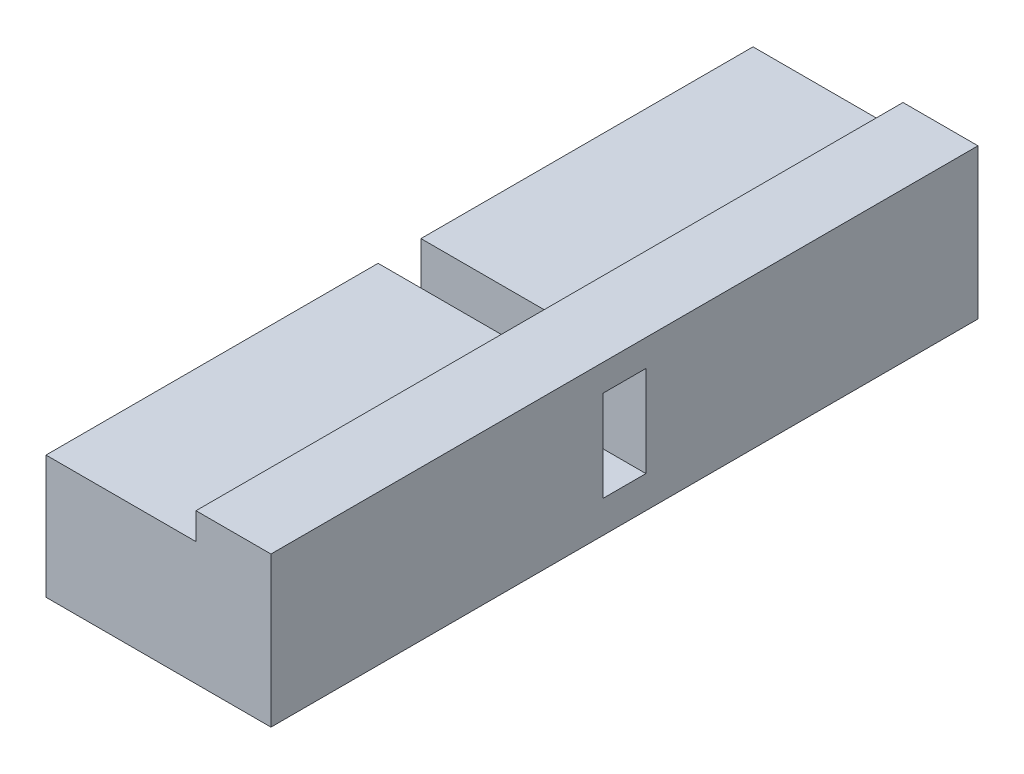
SolidWorks part; units mm, degrees
ref_plane "Front Plane" through (0, 0, 0) normal (0, 0, 1) x (1, 0, 0)
ref_plane "Top Plane" through (0, 0, 0) normal (0, 1, 0) x (1, 0, 0)
ref_plane "Right Plane" through (0, 0, 0) normal (1, 0, 0) x (0, 0, -1)
sketch "SK_P01_Carrier" plane through (0, 0, 0) normal (0, 1, 0) x (1, 0, 0)
  line L0 (-10.5, -33) -> (10.5, -33)
  line L1 (10.5, -33) -> (10.5, 33)
  line L2 (10.5, 33) -> (-10.5, 33)
  line L3 (-10.5, 33) -> (-10.5, -33)
extrude "P01_Carrier" add sketch "SK_P01_Carrier" along normal blind 3
sketch "SK_P02_WAGO221415GNDstar" plane through (0, 0, 0) normal (0, 1, 0) x (1, 0, 0)
  line L0 (-10.5, 2) -> (10.5, 2)
  line L1 (10.5, 2) -> (10.5, 33)
  line L2 (10.5, 33) -> (-10.5, 33)
  line L3 (-10.5, 33) -> (-10.5, 2)
extrude "P02_WAGO221415GNDstar" add sketch "SK_P02_WAGO221415GNDstar" along normal blind 8.5 from offset 3
sketch "SK_P03_WAGO221415packnode" plane through (0, 0, 0) normal (0, 1, 0) x (1, 0, 0)
  line L0 (-10.5, -33) -> (10.5, -33)
  line L1 (10.5, -33) -> (10.5, -2)
  line L2 (10.5, -2) -> (-10.5, -2)
  line L3 (-10.5, -2) -> (-10.5, -33)
extrude "P03_WAGO221415packnode" add sketch "SK_P03_WAGO221415packnode" along normal blind 8.5 from offset 3
sketch "SK_P04_Levers" plane through (0, 0, 0) normal (0, 1, 0) x (1, 0, 0)
  line L0 (3.5, -33) -> (10.5, -33)
  line L1 (10.5, -33) -> (10.5, 33)
  line L2 (10.5, 33) -> (3.5, 33)
  line L3 (3.5, 33) -> (3.5, -33)
extrude "P04_Levers" add sketch "SK_P04_Levers" along normal blind 2.5 from offset 11.5
